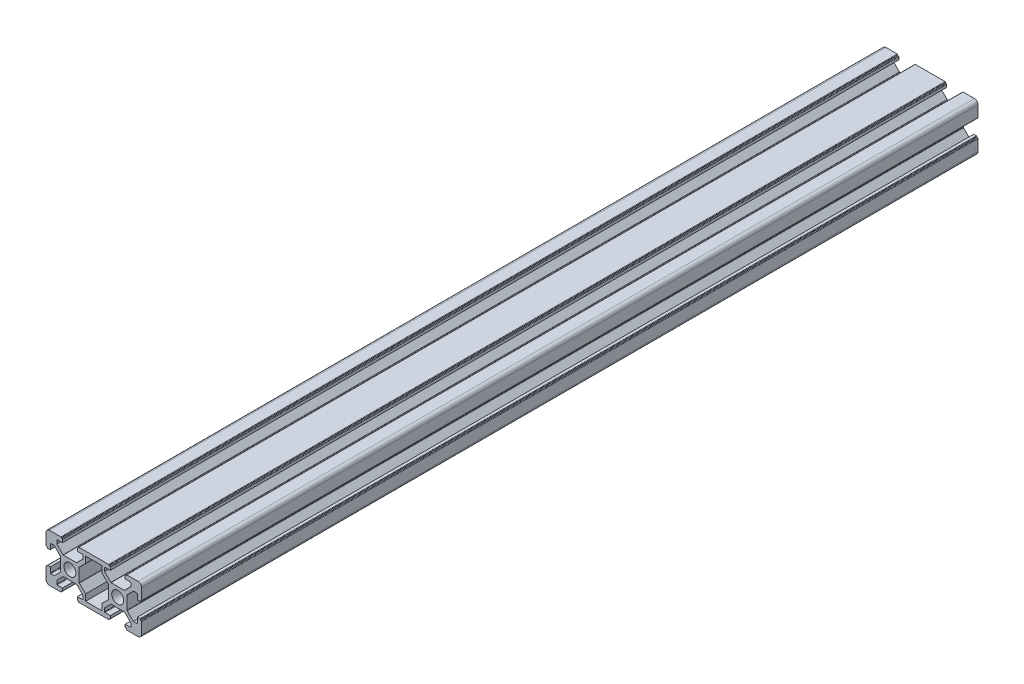
SolidWorks part; units mm, degrees
ref_plane "前视基准面" through (0, 0, 0) normal (0, 0, 1) x (1, 0, 0)
ref_plane "上视基准面" through (0, 0, 0) normal (0, 1, 0) x (1, 0, 0)
ref_plane "右视基准面" through (0, 0, 0) normal (1, 0, 0) x (0, 0, -1)
sketch "Sketch1" plane through (0, 0, 0) normal (0, 0, 1) x (1, 0, 0)
  line L0 (-8.5, 10) -> (-3.8, 10)
  line L3 (-8.5, -10) -> (-3.8, -10)
  line L5 (-10, 8.5) -> (-10, 3.8)
  line L6 (-2.7565, 3.9) -> (2.7565, 3.9)
  line L9 (-2.7565, -3.9) -> (2.7565, -3.9)
  line L10 (3.9, 2.7565) -> (3.9, -2.7565)
  line L11 (-3.9, 2.7565) -> (-3.9, -2.7565)
  line L12 (-3.9586, -2.8979) -> (-6.5607, -5.5)
  line L13 (3.6, 9.7) -> (3.6, 9.8)
  line L14 (3.1, -8.2) -> (5.3, -8.2)
  line L15 (-2.8979, -3.9586) -> (-5.5, -6.5607)
  line L16 (-3.1, -8.2) -> (-3.1, -9.3)
  line L17 (3.1, -8.2) -> (3.1, -9.3)
  line L18 (-5.5, -6.5607) -> (-5.5, -8)
  line L19 (5.5, -6.5607) -> (5.5, -8)
  line L20 (-5.3, -8.2) -> (-3.1, -8.2)
  line L21 (-3.4, -9.5) -> (-3.3, -9.5)
  line L22 (3.8, -10) -> (8.5, -10)
  line L23 (3.3, -9.5) -> (3.4, -9.5)
  line L24 (-3.6, -9.7) -> (-3.6, -9.8)
  line L25 (3.6, -9.7) -> (3.6, -9.8)
  line L26 (-6.5607, -5.5) -> (-8, -5.5)
  line L27 (-9.7, -3.6) -> (-9.8, -3.6)
  line L28 (-9.5, -3.4) -> (-9.5, -3.3)
  line L29 (-8.2, -3.1) -> (-9.3, -3.1)
  line L30 (-8.2, -5.3) -> (-8.2, -3.1)
  line L31 (-10, -3.8) -> (-10, -8.5)
  line L33 (3.8, 10) -> (8.5, 10)
  line L34 (2.8979, -3.9586) -> (5.5, -6.5607)
  line L40 (3.9586, -2.8979) -> (6.5607, -5.5)
  line L41 (3.3, 9.5) -> (3.4, 9.5)
  line L42 (30, 8.5) -> (30, 3.8)
  line L43 (3.1, 8.2) -> (3.1, 9.3)
  line L44 (3.1, 8.2) -> (5.3, 8.2)
  line L45 (5.5, 6.5607) -> (5.5, 8)
  line L46 (2.8979, 3.9586) -> (5.5, 6.5607)
  line L52 (3.9586, 2.8979) -> (6.5607, 5.5)
  line L53 (-3.6, 9.7) -> (-3.6, 9.8)
  line L54 (-3.4, 9.5) -> (-3.3, 9.5)
  line L55 (-3.1, 8.2) -> (-3.1, 9.3)
  line L56 (-5.3, 8.2) -> (-3.1, 8.2)
  line L57 (-5.5, 6.5607) -> (-5.5, 8)
  line L58 (-2.8979, 3.9586) -> (-5.5, 6.5607)
  line L59 (-9.5, 3.4) -> (-9.5, 3.3)
  line L60 (-9.7, 3.6) -> (-9.8, 3.6)
  line L61 (-8.2, 3.1) -> (-9.3, 3.1)
  line L62 (-8.2, 5.3) -> (-8.2, 3.1)
  line L63 (-6.5607, 5.5) -> (-8, 5.5)
  line L64 (-3.9586, 2.8979) -> (-6.5607, 5.5)
  line L65 (29.7, 3.6) -> (29.8, 3.6)
  line L66 (29.5, 3.4) -> (29.5, 3.3)
  line L67 (28.2, 3.1) -> (29.3, 3.1)
  line L68 (28.2, 5.3) -> (28.2, 3.1)
  line L69 (26.5607, 5.5) -> (28, 5.5)
  line L70 (23.9586, 2.8979) -> (26.5607, 5.5)
  line L71 (23.9, 2.7565) -> (23.9, -2.7565)
  line L72 (23.9586, -2.8979) -> (26.5607, -5.5)
  line L73 (26.5607, -5.5) -> (28, -5.5)
  line L74 (28.2, -5.3) -> (28.2, -3.1)
  line L75 (28.2, -3.1) -> (29.3, -3.1)
  line L76 (29.5, -3.4) -> (29.5, -3.3)
  line L77 (29.7, -3.6) -> (29.8, -3.6)
  line L78 (30, -3.8) -> (30, -8.5)
  line L79 (28.5, -10) -> (23.8, -10)
  line L80 (23.6, -9.7) -> (23.6, -9.8)
  line L81 (23.4, -9.5) -> (23.3, -9.5)
  line L82 (23.1, -8.2) -> (23.1, -9.3)
  line L83 (25.3, -8.2) -> (23.1, -8.2)
  line L84 (25.5, -6.5607) -> (25.5, -8)
  line L85 (22.8979, -3.9586) -> (25.5, -6.5607)
  line L86 (22.7565, -3.9) -> (17.2435, -3.9)
  line L87 (17.1021, -3.9586) -> (14.5, -6.5607)
  line L88 (14.5, -6.5607) -> (14.5, -8)
  line L89 (16.9, -8.2) -> (14.7, -8.2)
  line L90 (16.9, -8.2) -> (16.9, -9.3)
  line L91 (16.7, -9.5) -> (16.6, -9.5)
  line L92 (16.4, -9.7) -> (16.4, -9.8)
  line L93 (16.2, -10) -> (11.5, -10)
  line L94 (13.4393, 5.5) -> (13.4393, 8.2)
  line L96 (6.5607, 5.5) -> (6.5607, 8.2)
  line L97 (6.5607, 8.2) -> (13.4393, 8.2)
  line L99 (16.0414, -2.8979) -> (13.4393, -5.5)
  line L100 (16.1, 2.7565) -> (16.1, -2.7565)
  line L101 (16.0414, 2.8979) -> (13.4393, 5.5)
  line L107 (16.2, 10) -> (11.5, 10)
  line L108 (16.4, 9.7) -> (16.4, 9.8)
  line L109 (16.7, 9.5) -> (16.6, 9.5)
  line L110 (16.9, 8.2) -> (16.9, 9.3)
  line L111 (16.9, 8.2) -> (14.7, 8.2)
  line L112 (14.5, 6.5607) -> (14.5, 8)
  line L113 (17.1021, 3.9586) -> (14.5, 6.5607)
  line L114 (22.7565, 3.9) -> (17.2435, 3.9)
  line L115 (22.8979, 3.9586) -> (25.5, 6.5607)
  line L116 (25.5, 6.5607) -> (25.5, 8)
  line L117 (25.3, 8.2) -> (23.1, 8.2)
  line L118 (23.1, 8.2) -> (23.1, 9.3)
  line L119 (23.4, 9.5) -> (23.3, 9.5)
  line L120 (23.6, 9.7) -> (23.6, 9.8)
  line L121 (28.5, 10) -> (23.8, 10)
  line L122 (13.4393, -5.5) -> (13.4393, -8.2)
  line L124 (6.5607, -5.5) -> (6.5607, -8.2)
  line L125 (6.5607, -8.2) -> (13.4393, -8.2)
  line L127 (8.5, 10) -> (11.5, 10)
  line L128 (8.5, -10) -> (11.5, -10)
  arc A3 (-8.5, -10) -> (-10, -8.5) centre (-8.5, -8.5) cw
  arc A4 (-10, 8.5) -> (-8.5, 10) centre (-8.5, 8.5) cw
  arc A5 (3.4, -9.5) -> (3.6, -9.7) centre (3.4, -9.7) cw
  arc A6 (3.8, -10) -> (3.6, -9.8) centre (3.8, -9.8) cw
  arc A7 (3.3, -9.5) -> (3.1, -9.3) centre (3.3, -9.3) cw
  arc A8 (5.3, -8.2) -> (5.5, -8) centre (5.3, -8) ccw
  arc A9 (-3.9, -2.7565) -> (-3.9586, -2.8979) centre (-4.1, -2.7565) cw
  arc A10 (-3.9, 2.7565) -> (-3.9586, 2.8979) centre (-4.1, 2.7565) ccw
  arc A11 (-2.7565, 3.9) -> (-2.8979, 3.9586) centre (-2.7565, 4.1) cw
  arc A12 (2.7565, 3.9) -> (2.8979, 3.9586) centre (2.7565, 4.1) ccw
  arc A13 (3.9586, 2.8979) -> (3.9, 2.7565) centre (4.1, 2.7565) ccw
  arc A14 (3.9, -2.7565) -> (3.9586, -2.8979) centre (4.1, -2.7565) ccw
  arc A15 (-2.8979, -3.9586) -> (-2.7565, -3.9) centre (-2.7565, -4.1) cw
  arc A16 (2.7565, -3.9) -> (2.8979, -3.9586) centre (2.7565, -4.1) cw
  arc A17 (-3.6, -9.8) -> (-3.8, -10) centre (-3.8, -9.8) cw
  arc A18 (-3.3, -9.5) -> (-3.1, -9.3) centre (-3.3, -9.3) ccw
  arc A19 (-3.6, -9.7) -> (-3.4, -9.5) centre (-3.4, -9.7) cw
  arc A20 (-8.2, 5.3) -> (-8, 5.5) centre (-8, 5.3) cw
  arc A23 (-8.2, -5.3) -> (-8, -5.5) centre (-8, -5.3) ccw
  arc A24 (-5.3, -8.2) -> (-5.5, -8) centre (-5.3, -8) cw
  arc A31 (3.1, 9.3) -> (3.3, 9.5) centre (3.3, 9.3) cw
  arc A32 (3.6, 9.8) -> (3.8, 10) centre (3.8, 9.8) cw
  arc A33 (3.6, 9.7) -> (3.4, 9.5) centre (3.4, 9.7) cw
  arc A34 (-3.8, 10) -> (-3.6, 9.8) centre (-3.8, 9.8) cw
  arc A35 (-3.3, 9.5) -> (-3.1, 9.3) centre (-3.3, 9.3) cw
  arc A36 (-3.4, 9.5) -> (-3.6, 9.7) centre (-3.4, 9.7) cw
  arc A37 (5.5, 8) -> (5.3, 8.2) centre (5.3, 8) ccw
  arc A38 (-5.5, 8) -> (-5.3, 8.2) centre (-5.3, 8) cw
  arc A39 (-10, 3.8) -> (-9.8, 3.6) centre (-9.8, 3.8) ccw
  arc A40 (-9.5, 3.3) -> (-9.3, 3.1) centre (-9.3, 3.3) ccw
  arc A41 (-9.7, 3.6) -> (-9.5, 3.4) centre (-9.7, 3.4) cw
  arc A42 (-10, -3.8) -> (-9.8, -3.6) centre (-9.8, -3.8) cw
  arc A43 (-9.5, -3.3) -> (-9.3, -3.1) centre (-9.3, -3.3) cw
  arc A44 (-9.5, -3.4) -> (-9.7, -3.6) centre (-9.7, -3.4) cw
  arc A45 (30, 8.5) -> (28.5, 10) centre (28.5, 8.5) ccw
  arc A46 (30, 3.8) -> (29.8, 3.6) centre (29.8, 3.8) cw
  arc A47 (29.7, 3.6) -> (29.5, 3.4) centre (29.7, 3.4) ccw
  arc A48 (29.5, 3.3) -> (29.3, 3.1) centre (29.3, 3.3) cw
  arc A49 (28.2, 5.3) -> (28, 5.5) centre (28, 5.3) ccw
  arc A50 (23.9, 2.7565) -> (23.9586, 2.8979) centre (24.1, 2.7565) cw
  arc A51 (23.9, -2.7565) -> (23.9586, -2.8979) centre (24.1, -2.7565) ccw
  arc A52 (28.2, -5.3) -> (28, -5.5) centre (28, -5.3) cw
  arc A53 (29.5, -3.3) -> (29.3, -3.1) centre (29.3, -3.3) ccw
  arc A54 (29.5, -3.4) -> (29.7, -3.6) centre (29.7, -3.4) ccw
  arc A55 (30, -3.8) -> (29.8, -3.6) centre (29.8, -3.8) ccw
  arc A56 (28.5, -10) -> (30, -8.5) centre (28.5, -8.5) ccw
  arc A57 (23.6, -9.8) -> (23.8, -10) centre (23.8, -9.8) ccw
  arc A58 (23.6, -9.7) -> (23.4, -9.5) centre (23.4, -9.7) ccw
  arc A59 (23.3, -9.5) -> (23.1, -9.3) centre (23.3, -9.3) cw
  arc A60 (25.3, -8.2) -> (25.5, -8) centre (25.3, -8) ccw
  arc A61 (22.8979, -3.9586) -> (22.7565, -3.9) centre (22.7565, -4.1) ccw
  arc A62 (17.2435, -3.9) -> (17.1021, -3.9586) centre (17.2435, -4.1) ccw
  arc A63 (14.7, -8.2) -> (14.5, -8) centre (14.7, -8) cw
  arc A64 (16.7, -9.5) -> (16.9, -9.3) centre (16.7, -9.3) ccw
  arc A65 (16.6, -9.5) -> (16.4, -9.7) centre (16.6, -9.7) ccw
  arc A66 (16.2, -10) -> (16.4, -9.8) centre (16.2, -9.8) ccw
  arc A72 (16.1, -2.7565) -> (16.0414, -2.8979) centre (15.9, -2.7565) cw
  arc A73 (16.0414, 2.8979) -> (16.1, 2.7565) centre (15.9, 2.7565) cw
  arc A79 (16.4, 9.8) -> (16.2, 10) centre (16.2, 9.8) ccw
  arc A80 (16.4, 9.7) -> (16.6, 9.5) centre (16.6, 9.7) ccw
  arc A81 (16.9, 9.3) -> (16.7, 9.5) centre (16.7, 9.3) ccw
  arc A82 (14.5, 8) -> (14.7, 8.2) centre (14.7, 8) cw
  arc A83 (17.2435, 3.9) -> (17.1021, 3.9586) centre (17.2435, 4.1) cw
  arc A84 (22.7565, 3.9) -> (22.8979, 3.9586) centre (22.7565, 4.1) ccw
  arc A85 (25.5, 8) -> (25.3, 8.2) centre (25.3, 8) ccw
  arc A86 (23.3, 9.5) -> (23.1, 9.3) centre (23.3, 9.3) ccw
  arc A87 (23.4, 9.5) -> (23.6, 9.7) centre (23.4, 9.7) ccw
  arc A88 (23.8, 10) -> (23.6, 9.8) centre (23.8, 9.8) ccw
  point P11 (3.9, 3.9)
  point P19 (3.3697, 4.4303)
  point P20 (-10.6428, -10.6428)
  point P25 (-11.1731, -10.1124)
  point P26 (4.4303, 3.3697)
  point P28 (-10.1124, -11.1731)
  dimension "D3" = 0.2
  dimension "D4" = 0.2
  dimension "D5" = 0.2
  dimension "D8" = 0.2
  dimension "D9" = 0.2
  dimension "D10" = 0.2
  dimension "D6" = 1.8
  dimension "D7" = 0.5
extrude "Boss-Extrude1" add sketch "Sketch1" along normal blind 350
ref_plane "hole" through (0, 0, 350) normal (0, 0, 1) x (1, 0, 0)
sketch "Sketch2" plane through (0, 0, 350) normal (0, 0, 1) x (1, 0, 0)
  circle A0 centre (0, 0) radius 2.5
  circle A1 centre (20, 0) radius 2.5
  dimension "D1" = 5
extrude "Cut-Extrude1" cut sketch "Sketch2" against normal through all
